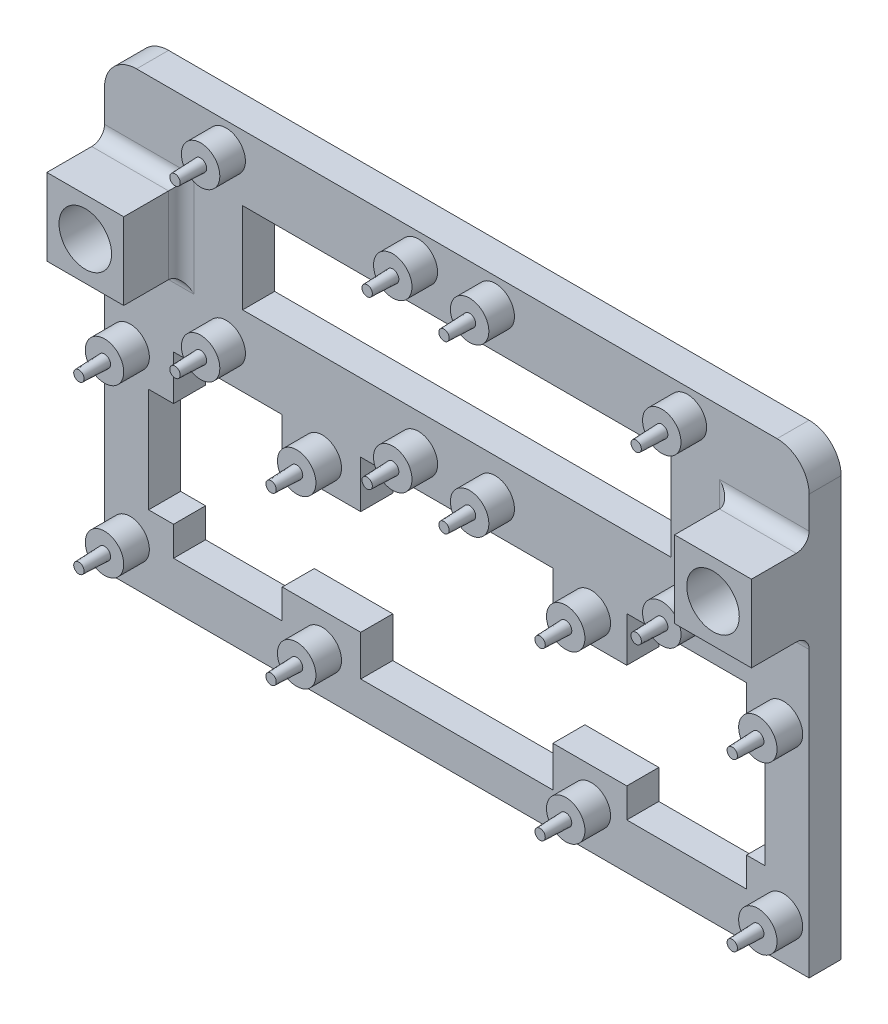
SolidWorks part; units mm, degrees
ref_plane "Ebene vorne" through (0, 0, 0) normal (0, 0, 1) x (1, 0, 0)
ref_plane "Ebene oben" through (0, 0, 0) normal (0, 1, 0) x (1, 0, 0)
ref_plane "Ebene rechts" through (0, 0, 0) normal (1, 0, 0) x (0, 0, -1)
sketch "Skizze1" plane through (0, 0, 0) normal (0, 0, 1) x (1, 0, 0)
  line L1 (-55, -85) -> (55, -85)
  line L2 (-55, -85) -> (-55, 85)
  line L3 (-55, 85) -> (55, 85)
  line L4 (55, -85) -> (55, 85)
  line L5 (-55, -85) -> (55, 85) construction
  line L6 (-55, 85) -> (55, -85) construction
  point P0 (0, 0)
  dimension "D1" = 110
  dimension "D2" = 170
extrude "Aufsatz-Linear austragen1" add sketch "Skizze1" along normal blind 5
fillet "Verrundung1" radius 5 4 edges at (-55, -85, 2.5) (55, -85, 2.5) (55, 85, 2.5) (-55, 85, 2.5)
sketch "Skizze7" plane through (0, 0, 5) normal (0, 0, 1) x (1, 0, 0)
  line L0 (-55, 80) -> (-55, -80) construction
  line L1 (-55, 73) -> (-43, 73)
  line L2 (-55, 73) -> (-55, 61)
  line L3 (-55, 61) -> (-43, 61)
  line L4 (-43, 73) -> (-43, 61)
  line L5 (50, 85) -> (-50, 85) construction
  line L18 (0, 85) -> (0, -85) construction
  line L19 (-50, -85) -> (50, -85) construction
  line L20 (-55, 0) -> (55, 0) construction
  line L21 (55, -80) -> (55, 80) construction
  line L22 (43, 73) -> (43, 61)
  line L23 (55, 61) -> (43, 61)
  line L24 (55, 73) -> (55, 61)
  line L25 (55, 73) -> (43, 73)
  line L26 (55, -73) -> (43, -73)
  line L27 (55, -73) -> (55, -61)
  line L28 (55, -61) -> (43, -61)
  line L29 (43, -73) -> (43, -61)
  line L30 (-43, -73) -> (-43, -61)
  line L31 (-55, -61) -> (-43, -61)
  line L32 (-55, -73) -> (-55, -61)
  line L33 (-55, -73) -> (-43, -73)
  dimension "D1" = 12
  dimension "D2" = 12
extrude "Aufsatz-Linear austragen3" add sketch "Skizze7" along normal blind 28
fillet "Verrundung2" radius 2 12 edges at (-49, 73, 5) (-49, 61, 5) (-43, 67, 5) (-49, -61, 5) (-43, -67, 5) (-49, -73, 5) (49, -73, 5) (43, -67, 5) (49, -61, 5) (49, 61, 5) (43, 67, 5) (49, 73, 5)
sketch "Skizze8" plane through (0, 0, 33) normal (0, 0, 1) x (1, 0, 0)
  line L0 (-55, 73) -> (-43, 61) construction
  line L1 (-55, 61) -> (-43, 73) construction
  line L5 (-55, 31.954) -> (-55, -16.1316) construction
  line L8 (-55, 59) -> (-55, -59) construction
  circle A1 centre (-49, 67) radius 4.1
  dimension "D1" = 8.2
extrude "Schnitt-Linear austragen3" cut sketch "Skizze8" against normal through all
pattern_linear "Lineares Muster1" count 2 spacing 134 along (0, -1, 0) count 2 spacing 98 along (1, 0, 0) of "Schnitt-Linear austragen3"
sketch "Skizze9" plane through (0, 0, 5) normal (0, 0, 1) x (1, 0, 0)
  line L0 (0, 85) -> (0, -85) construction
  line L1 (-28, -77) -> (28, -77) construction
  line L2 (-28, -77) -> (-28, 12) construction
  line L3 (-28, 12) -> (28, 12) construction
  line L4 (28, -77) -> (28, 12) construction
  line L5 (-28, -77) -> (28, 12) construction
  line L6 (-28, 12) -> (28, -77) construction
  line L11 (50, 85) -> (-50, 85) construction
  line L12 (-50, -85) -> (50, -85) construction
  line L13 (-55, 59) -> (-55, -59) construction
  line L14 (-51, 21) -> (-21, 21) construction
  line L15 (-51, 21) -> (-51, 47) construction
  line L16 (-51, 47) -> (-21, 47) construction
  line L17 (-21, 21) -> (-21, 47) construction
  line L18 (-51, 21) -> (-21, 47) construction
  line L19 (-51, 47) -> (-21, 21) construction
  line L21 (-36, 55) -> (-6, 55) construction
  line L22 (-36, 55) -> (-36, 81) construction
  line L23 (-36, 81) -> (-6, 81) construction
  line L24 (-6, 55) -> (-6, 81) construction
  line L25 (-36, 55) -> (-6, 81) construction
  line L26 (-36, 81) -> (-6, 55) construction
  line L27 (51, 47) -> (21, 47) construction
  line L28 (21, 21) -> (21, 47) construction
  line L29 (51, 21) -> (21, 21) construction
  line L30 (51, 21) -> (51, 47) construction
  line L31 (36, 81) -> (6, 81) construction
  line L32 (6, 55) -> (6, 81) construction
  line L33 (36, 55) -> (6, 55) construction
  line L34 (36, 55) -> (36, 81) construction
  circle A0 centre (24.75, -73.75) radius 3
  circle A1 centre (24.75, -16.25) radius 3
  circle A2 centre (-24.75, -16.25) radius 3
  circle A3 centre (-24.75, -73.75) radius 3
  circle A4 centre (-36, 81) radius 3
  circle A5 centre (-6, 81) radius 3
  circle A6 centre (-36, 55) radius 3
  circle A7 centre (-6, 55) radius 3
  circle A8 centre (6, 81) radius 3
  circle A9 centre (36, 81) radius 3
  circle A10 centre (36, 55) radius 3
  circle A11 centre (6, 55) radius 3
  circle A12 centre (21, 47) radius 3
  circle A13 centre (51, 47) radius 3
  circle A14 centre (51, 21) radius 3
  circle A15 centre (21, 21) radius 3
  circle A16 centre (-21, 47) radius 3
  circle A17 centre (-51, 47) radius 3
  circle A18 centre (-51, 21) radius 3
  circle A19 centre (-21, 21) radius 3
  point P0 (0, 0)
  point P5 (0, -32.5)
  point P21 (-36, 34)
  point P28 (-21, 68)
  dimension "D3" = 3.25
  dimension "D4" = 6
  dimension "D5" = 57.5
  dimension "D17" = 6
  dimension "D1" = 56
  dimension "D2" = 89
  dimension "D6" = 3.25
  dimension "D7" = 8
  dimension "D8" = 28
  dimension "D9" = 26
  dimension "D10" = 30
  dimension "D11" = 4
  dimension "D12" = 38
  dimension "D13" = 26
  dimension "D14" = 30
  dimension "D15" = 4
  dimension "D16" = 19
extrude "Aufsatz-Linear austragen4" add sketch "Skizze9" along normal blind 4
sketch "Skizze10" plane through (0, 0, 9) normal (0, 0, 1) x (1, 0, 0)
  line L0 (0, -85) -> (0, 85) construction
  line L1 (-50, -85) -> (50, -85) construction
  line L2 (50, 85) -> (-50, 85) construction
  circle A0 centre (24.75, -73.75) radius 0.95
  circle A1 centre (24.75, -16.25) radius 0.95
  circle A2 centre (-24.75, -16.25) radius 0.95
  circle A3 centre (-24.75, -73.75) radius 0.95
  circle A4 centre (-51, 47) radius 0.95
  circle A5 centre (-51, 21) radius 0.95
  circle A6 centre (-21, 21) radius 0.95
  circle A7 centre (-21, 47) radius 0.95
  circle A8 centre (-36, 55) radius 0.95
  circle A9 centre (-6, 55) radius 0.95
  circle A10 centre (6, 55) radius 0.95
  circle A11 centre (-36, 81) radius 0.95
  circle A12 centre (-6, 81) radius 0.95
  circle A13 centre (6, 81) radius 0.95
  circle A14 centre (36, 81) radius 0.95
  circle A15 centre (36, 55) radius 0.95
  circle A16 centre (21, 47) radius 0.95
  circle A17 centre (51, 47) radius 0.95
  circle A18 centre (21, 21) radius 0.95
  circle A19 centre (51, 21) radius 0.95
  dimension "D1" = 1.9
extrude "Aufsatz-Linear austragen5" add sketch "Skizze10" along normal blind 4 draft 2
chamfer "Fase1" distance 1.2 angle 45 4 edges at (-44.9, 67, 33) (-44.9, -67, 33) (53.1, -67, 33) (53.1, 67, 33)
sketch "Skizze11" plane through (0, 0, 5) normal (0, 0, 1) x (1, 0, 0)
  line L0 (0, 85) -> (0, -85) construction
  line L1 (-15, 20) -> (15, 20)
  line L2 (-15, 20) -> (-15, 50)
  line L3 (-15, 50) -> (15, 50)
  line L4 (15, 20) -> (15, 50)
  line L5 (-15, 20) -> (15, 50) construction
  line L6 (-15, 50) -> (15, 20) construction
  line L7 (50, 85) -> (-50, 85) construction
  line L8 (-50, -85) -> (50, -85) construction
  point P0 (0, 35)
  dimension "D1" = 30
  dimension "D2" = 30
  dimension "D3" = 35
extrude "Schnitt-Linear austragen4" cut sketch "Skizze11" against normal through all
sketch "Skizze12" plane through (0, 0, 5) normal (0, 0, 1) x (1, 0, 0)
  line L1 (-63.6234, -88.2079) -> (63.6234, -88.2079)
  line L2 (-63.6234, -88.2079) -> (-63.6234, 14.5778)
  line L3 (-63.6234, 14.5778) -> (63.6234, 14.5778)
  line L4 (63.6234, -88.2079) -> (63.6234, 14.5778)
  line L5 (-63.6234, -88.2079) -> (63.6234, 14.5778) construction
  line L6 (-63.6234, 14.5778) -> (63.6234, -88.2079) construction
  point P0 (0, -36.8151)
extrude "Schnitt-Linear austragen5" cut sketch "Skizze12" against normal through all and the other way through all
sketch "Skizze13" plane through (0, 0, 33) normal (0, 0, 1) x (1, 0, 0)
  line L1 (-67.5627, 55.7209) -> (64.6534, 55.7209)
  line L2 (-67.5627, 55.7209) -> (-67.5627, 78.0359)
  line L3 (-67.5627, 78.0359) -> (64.6534, 78.0359)
  line L4 (64.6534, 55.7209) -> (64.6534, 78.0359)
  line L5 (-67.5627, 55.7209) -> (64.6534, 78.0359) construction
  line L6 (-67.5627, 78.0359) -> (64.6534, 55.7209) construction
  point P0 (-1.4547, 66.8784)
extrude "Schnitt-Linear austragen6" cut sketch "Skizze13" against normal blind 19
sketch "Skizze14" plane through (0, 0, 5) normal (0, 0, 1) x (1, 0, 0)
  line L1 (-44.2247, 21.7167) -> (-27.2539, 21.7167)
  line L2 (-44.2247, 21.7167) -> (-44.2247, 49.6178)
  line L3 (-44.2247, 49.6178) -> (-27.2539, 49.6178)
  line L4 (-27.2539, 21.7167) -> (-27.2539, 49.6178)
  line L5 (-44.2247, 21.7167) -> (-27.2539, 49.6178) construction
  line L6 (-44.2247, 49.6178) -> (-27.2539, 21.7167) construction
  line L7 (-33.4382, 60.692) -> (33.4382, 60.692)
  line L8 (-33.4382, 60.692) -> (-33.4382, 74.7864)
  line L9 (-33.4382, 74.7864) -> (33.4382, 74.7864)
  line L10 (33.4382, 60.692) -> (33.4382, 74.7864)
  line L11 (-33.4382, 60.692) -> (33.4382, 74.7864) construction
  line L12 (-33.4382, 74.7864) -> (33.4382, 60.692) construction
  line L13 (26.5348, 21.7167) -> (45.2315, 21.7167)
  line L14 (26.5348, 21.7167) -> (26.5348, 49.6178)
  line L15 (26.5348, 49.6178) -> (45.2315, 49.6178)
  line L16 (45.2315, 21.7167) -> (45.2315, 49.6178)
  line L17 (26.5348, 21.7167) -> (45.2315, 49.6178) construction
  line L18 (26.5348, 49.6178) -> (45.2315, 21.7167) construction
  line L30 (11.9571, 24.7102) -> (26.5348, 42.0058) construction
  line L31 (11.9571, 42.0058) -> (26.5348, 24.7102) construction
  line L34 (-27.2539, 24.7102) -> (-12.3491, 42.0058) construction
  line L35 (-27.2539, 42.0058) -> (-12.3491, 24.7102) construction
  point P0 (-35.7393, 35.6673)
  point P5 (0, 67.7392)
  point P10 (35.8831, 35.6673)
  point P15 (-19.8015, 33.358)
  point P22 (19.2459, 33.358)
extrude "Schnitt-Linear austragen7" cut sketch "Skizze14" against normal through all
sketch "Skizze15" plane through (0, 0, 5) normal (0, 0, 1) x (1, 0, 0)
  line L1 (-48.119, 26.3162) -> (48.119, 26.3162)
  line L2 (-48.119, 26.3162) -> (-48.119, 42.6235)
  line L3 (-48.119, 42.6235) -> (48.119, 42.6235)
  line L4 (48.119, 26.3162) -> (48.119, 42.6235)
  line L5 (-48.119, 26.3162) -> (48.119, 42.6235) construction
  line L6 (-48.119, 42.6235) -> (48.119, 26.3162) construction
  point P0 (0, 34.4699)
extrude "Schnitt-Linear austragen8" cut sketch "Skizze15" against normal through all
